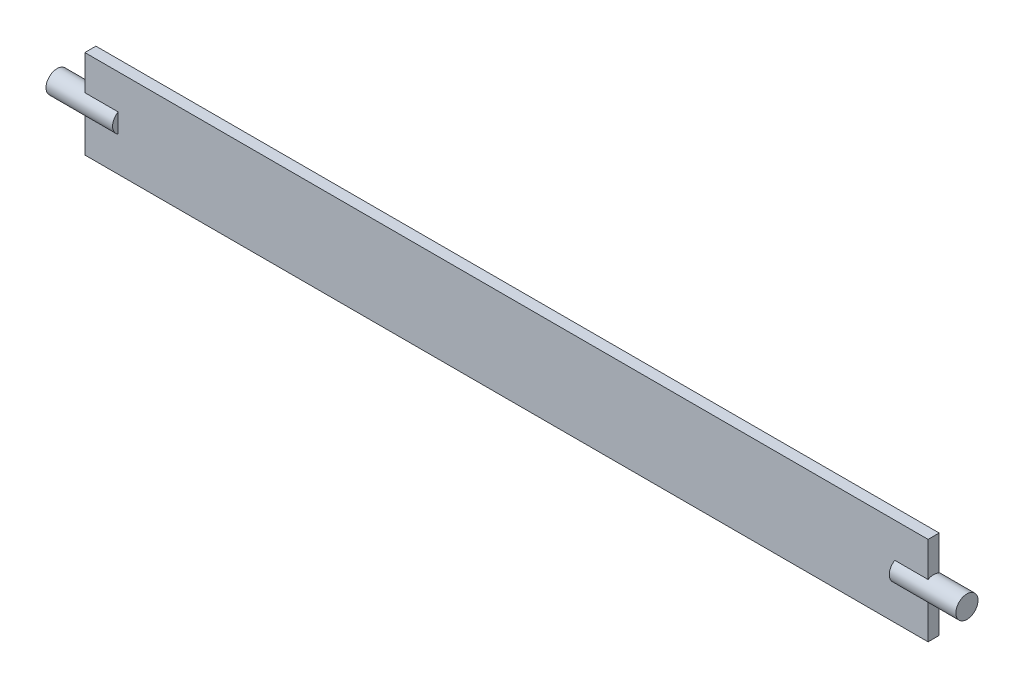
SolidWorks part; units mm, degrees
ref_plane "Front Plane" through (0, 0, 0) normal (0, 0, 1) x (1, 0, 0)
ref_plane "Top Plane" through (0, 0, 0) normal (0, 1, 0) x (1, 0, 0)
ref_plane "Right Plane" through (0, 0, 0) normal (1, 0, 0) x (0, 0, -1)
sketch "Sketch1" plane through (0, 0, 0) normal (0, 0, 1) x (1, 0, 0)
  line L1 (-190, 20) -> (190, 20)
  line L2 (-190, 20) -> (-190, -20)
  line L3 (-190, -20) -> (190, -20)
  line L4 (190, 20) -> (190, -20)
  line L5 (-190, 20) -> (190, -20) construction
  line L6 (-190, -20) -> (190, 20) construction
  point P0 (0, 0)
  dimension "D1" = 380
  dimension "D2" = 40
extrude "Boss-Extrude1" add sketch "Sketch1" against normal blind 5
sketch "Sketch2" plane through (-190, 0, 0) normal (-1, 0, 0) x (0, 0, 1)
  circle A0 centre (-2.5, 0) radius 5
  dimension "D1" = 10
extrude "Boss-Extrude2" add sketch "Sketch2" along normal mid plane 30
mirror "Mirror1" about plane through (0, 0, 0) normal (1, 0, 0) of "Boss-Extrude2"
